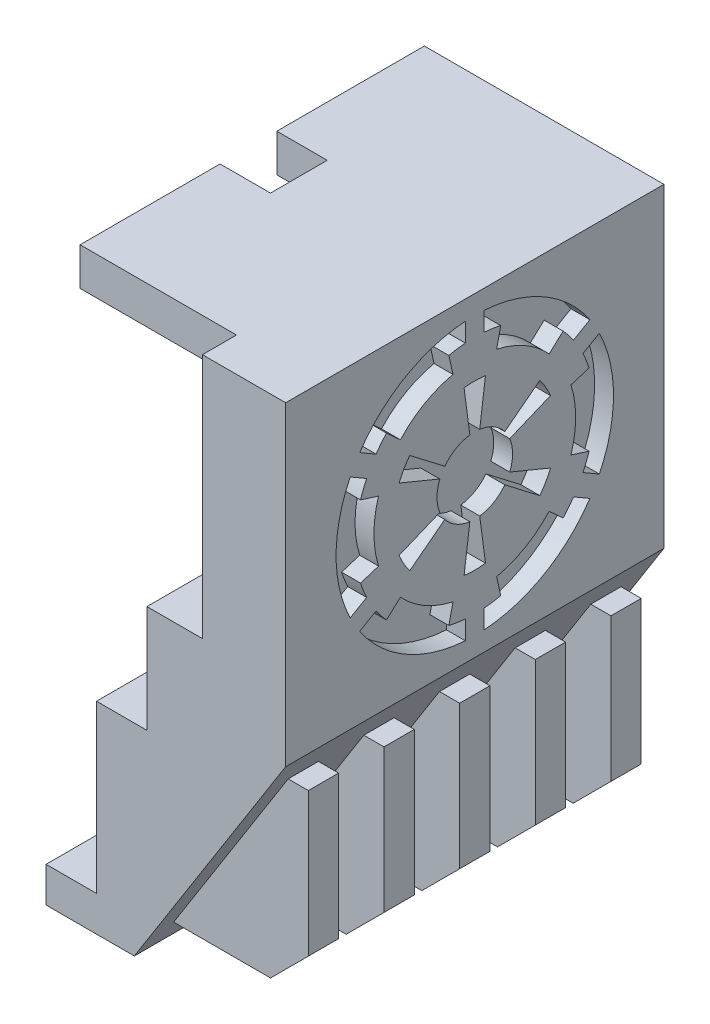
SolidWorks part; units mm, degrees
material "PE Low/Medium Density"
ref_plane "Front Plane" through (0, 0, 0) normal (0, 0, 1) x (1, 0, 0)
ref_plane "Top Plane" through (0, 0, 0) normal (0, 1, 0) x (1, 0, 0)
ref_plane "Right Plane" through (0, 0, 0) normal (1, 0, 0) x (0, 0, -1)
sketch "Sketch1" plane through (0, 0, 0) normal (1, 0, 0) x (0, 0, -1)
  line L2 (-15, -12.5) -> (15, -12.5)
  line L3 (-15, -12.5) -> (-15, 12.5)
  line L4 (-15, 12.5) -> (15, 12.5)
  line L5 (15, -12.5) -> (15, 12.5)
  line L6 (-15, -12.5) -> (15, 12.5) construction
  line L7 (-15, 12.5) -> (15, -12.5) construction
  point P1 (0, 0)
  dimension "D1" = 30
  dimension "D2" = 25
extrude "Boss-Extrude1" add sketch "Sketch1" along normal blind 3
sketch "Sketch2" plane through (0, 0, 0) normal (-1, 0, 0) x (0, 0, 1)
  line L0 (6, 9.5) -> (1.7, 9.5) construction
  line L1 (15, 12.5) -> (6, 12.5)
  line L2 (15, 12.5) -> (15, 9.5)
  line L3 (15, 9.5) -> (6, 9.5)
  line L4 (6, 12.5) -> (6, 9.5)
  line L5 (-15, 12.5) -> (15, 12.5) construction
  line L6 (1.7, 9.5) -> (-12.3, 9.5)
  line L7 (1.7, 9.5) -> (1.7, 12.5)
  line L8 (1.7, 12.5) -> (-12.3, 12.5)
  line L9 (-12.3, 9.5) -> (-12.3, 12.5)
  dimension "D1" = 9
  dimension "D2" = 3
  dimension "D3" = 4.3
  dimension "D4" = 14
extrude "Boss-Extrude2" add sketch "Sketch2" along normal blind 16
sketch "Sketch3" plane through (0, 0, 0) normal (-1, 0, 0) x (0, 0, 1)
  line L1 (1.7, 12.5) -> (6, 12.5)
  line L2 (1.7, 12.5) -> (1.7, 9.5)
  line L3 (1.7, 9.5) -> (6, 9.5)
  line L4 (6, 12.5) -> (6, 9.5)
extrude "Boss-Extrude3" add sketch "Sketch3" along normal blind 12
sketch "Sketch4" plane through (0, 0, 0) normal (-1, 0, 0) x (0, 0, 1)
  line L0 (15, 9.5) -> (15, -7) construction
  line L1 (15, 9.5) -> (15, -12.5) construction
  line L3 (15, -7) -> (-15, -7)
  line L4 (15, -7) -> (15, -12.5)
  line L5 (15, -12.5) -> (-15, -12.5)
  line L6 (-15, -7) -> (-15, -12.5)
  dimension "D1" = 16.5
extrude "Boss-Extrude4" add sketch "Sketch4" along normal blind 8
sketch "Sketch5" plane through (0, 0, 15) normal (0, 0, 1) x (1, 0, 0)
  line L0 (-8, -12.5) -> (-8, -31.5) construction
  line L1 (-12, -31.5) -> (-9, -31.5)
  line L2 (-9, -31.5) -> (3, -12.5)
  line L3 (3, -12.5) -> (-8, -12.5)
  line L4 (-8, -12.5) -> (-8, -15.5)
  line L5 (-8, -15.5) -> (-12, -15.5)
  line L6 (-12, -15.5) -> (-12, -31.5)
  line L7 (-9, -31.5) -> (-8, -31.5) construction
  dimension "D1" = 24.5
  dimension "D2" = 3
  dimension "D3" = 4
  dimension "D4" = 8.5
extrude "Boss-Extrude5" add sketch "Sketch5" against normal up to surface (30 mm away) up to face at (-1.6667, -2.3333, -15)
sketch "Sketch7" plane through (0, -31.5, 0) normal (0, -1, 0) x (1, 0, 0)
  line L0 (-9, -15) -> (-12, -15) construction
  line L1 (-12, 15) -> (-16, 15)
  line L2 (-12, 15) -> (-12, 6)
  line L3 (-12, 6) -> (-16, 6)
  line L4 (-16, 15) -> (-16, 6)
  line L5 (-12, 1.7) -> (-16, 1.7)
  line L6 (-12, 1.7) -> (-12, -15)
  line L7 (-12, -15) -> (-16, -15)
  line L8 (-16, 1.7) -> (-16, -15)
  line L9 (-16, -12.3) -> (-16, 1.7) construction
extrude "Boss-Extrude6" add sketch "Sketch7" against normal blind 3
sketch "Sketch9" plane through (0, 0, 15) normal (0, 0, 1) x (1, 0, 0)
  line L2 (0, -7) -> (-12, -7)
  line L3 (0, -7) -> (0, 9.5)
  line L4 (0, 9.5) -> (-12, 9.5)
  line L5 (-12, -7) -> (-12, 9.5)
sketch "Sketch10" plane through (7.7881, -4.9188, 0) normal (0.8455, -0.534, 0) x (0, 0, -1)
  line L0 (-7.2, -11.9666) -> (-7.2, -28.9666)
  line L1 (-13.2, -11.9666) -> (-10.8, -11.9666)
  line L2 (-13.2, -11.9666) -> (-13.2, -28.9666)
  line L3 (-13.2, -28.9666) -> (-10.8, -28.9666)
  line L4 (-10.8, -11.9666) -> (-10.8, -28.9666)
  line L5 (-7.2, -11.9666) -> (-4.8, -11.9666)
  line L6 (-4.8, -11.9666) -> (-4.8, -28.9666)
  line L7 (-7.2, -28.9666) -> (-4.8, -28.9666)
  line L8 (-1.2, -11.9666) -> (-1.2, -28.9666)
  line L9 (-1.2, -11.9666) -> (1.2, -11.9666)
  line L10 (1.2, -11.9666) -> (1.2, -28.9666)
  line L11 (-1.2, -28.9666) -> (1.2, -28.9666)
  line L12 (4.8, -11.9666) -> (4.8, -28.9666)
  line L13 (4.8, -11.9666) -> (7.2, -11.9666)
  line L14 (7.2, -11.9666) -> (7.2, -28.9666)
  line L15 (4.8, -28.9666) -> (7.2, -28.9666)
  line L16 (10.8, -11.9666) -> (10.8, -28.9666)
  line L17 (10.8, -11.9666) -> (13.2, -11.9666)
  line L18 (13.2, -11.9666) -> (13.2, -28.9666)
  line L19 (10.8, -28.9666) -> (13.2, -28.9666)
  line L20 (-15, -31.4388) -> (-15, -8.9666) construction
  line L25 (-15, -8.9666) -> (15, -8.9666) construction
  dimension "D1" = 5
  dimension "D2" = 2.4
  dimension "D3" = 1.8
  dimension "D4" = 17
  dimension "D5" = 3
sketch "Sketch11" plane through (3, 0, 0) normal (1, 0, 0) x (0, 0, -1)
  line L0 (-13.2, -15.0365) -> (-13.2, -29.4098) construction
  line L1 (-13.2, -29.4098) -> (-10.8, -29.4098) construction
  line L2 (-10.8, -15.0365) -> (-10.8, -29.4098) construction
  line L3 (-13.2, -15.0365) -> (-10.8, -15.0365) construction
  line L4 (-7.2, -15.0365) -> (-7.2, -29.4098) construction
  line L5 (-7.2, -29.4098) -> (-4.8, -29.4098) construction
  line L6 (-4.8, -15.0365) -> (-4.8, -29.4098) construction
  line L7 (-7.2, -15.0365) -> (-4.8, -15.0365) construction
  line L8 (-1.2, -15.0365) -> (-1.2, -29.4098) construction
  line L9 (-1.2, -29.4098) -> (1.2, -29.4098) construction
  line L10 (1.2, -15.0365) -> (1.2, -29.4098) construction
  line L11 (-1.2, -15.0365) -> (1.2, -15.0365) construction
  line L12 (4.8, -15.0365) -> (4.8, -29.4098) construction
  line L13 (4.8, -29.4098) -> (7.2, -29.4098) construction
  line L14 (7.2, -15.0365) -> (7.2, -29.4098) construction
  line L15 (4.8, -15.0365) -> (7.2, -15.0365) construction
  line L16 (10.8, -15.0365) -> (10.8, -29.4098) construction
  line L17 (10.8, -29.4098) -> (13.2, -29.4098) construction
  line L18 (13.2, -15.0365) -> (13.2, -29.4098) construction
  line L19 (10.8, -15.0365) -> (13.2, -15.0365) construction
  line L20 (-13.2, -15.0365) -> (-13.2, -29.4098)
  line L21 (-13.2, -29.4098) -> (-10.8, -29.4098)
  line L22 (-10.8, -15.0365) -> (-10.8, -29.4098)
  line L23 (-13.2, -15.0365) -> (-10.8, -15.0365)
  line L24 (-7.2, -15.0365) -> (-7.2, -29.4098)
  line L25 (-7.2, -29.4098) -> (-4.8, -29.4098)
  line L26 (-4.8, -15.0365) -> (-4.8, -29.4098)
  line L27 (-7.2, -15.0365) -> (-4.8, -15.0365)
  line L28 (-1.2, -15.0365) -> (-1.2, -29.4098)
  line L29 (-1.2, -29.4098) -> (1.2, -29.4098)
  line L30 (1.2, -15.0365) -> (1.2, -29.4098)
  line L31 (-1.2, -15.0365) -> (1.2, -15.0365)
  line L32 (4.8, -15.0365) -> (4.8, -29.4098)
  line L33 (4.8, -29.4098) -> (7.2, -29.4098)
  line L34 (7.2, -15.0365) -> (7.2, -29.4098)
  line L35 (4.8, -15.0365) -> (7.2, -15.0365)
  line L36 (10.8, -15.0365) -> (10.8, -29.4098)
  line L37 (10.8, -29.4098) -> (13.2, -29.4098)
  line L38 (13.2, -15.0365) -> (13.2, -29.4098)
  line L39 (10.8, -15.0365) -> (13.2, -15.0365)
  point P2 (-13.2, -22.2231)
extrude "Boss-Extrude8" add sketch "Sketch11" against normal up to surface (1.602 mm away)
chamfer "Chamfer1" distance 3 angle 45 5 edges at (3, -29.4098, -12) (3, -29.4098, -6) (3, -29.4098, 0) (3, -29.4098, 6) (3, -29.4098, 12)
sketch "Sketch12" plane through (3, 0, 0) normal (1, 0, 0) x (0, 0, -1)
  line L0 (0, 0) -> (0, 11) construction
  line L1 (-0.75, 10.9744) -> (-0.75, 9.4703)
  line L2 (0.75, 10.9744) -> (0.75, 9.4703)
  line L3 (-0.75, 9.4703) -> (0, 11) construction
  line L4 (0, 11) -> (0.75, 9.4703) construction
  line L5 (0, 0) -> (-3.5236, 15.8941) construction
  line L6 (0, 0) -> (3.5236, 15.8941) construction
  line L7 (3.5236, 15.8941) -> (0, 11) construction
  line L8 (0, 11) -> (-3.5236, 15.8941) construction
  line L9 (-3.5236, 15.8941) -> (3.5236, 15.8941) construction
  line L10 (-1.7315, 7.8104) -> (-2.0562, 9.2748)
  line L11 (1.7315, 7.8104) -> (2.0562, 9.2748)
  line L12 (0, 0) -> (-0.8484, 6.4444) construction
  line L13 (-0.8484, 6.4444) -> (0.8484, 6.4444) construction
  line L14 (0.8484, 6.4444) -> (0, 0) construction
  line L15 (-0.8484, 6.4444) -> (-0.3916, 2.9743)
  line L16 (0.8484, 6.4444) -> (0.3916, 2.9743)
  line L17 (9.1291, 6.1367) -> (7.8266, 5.3847)
  line L18 (9.8791, 4.8377) -> (8.5766, 4.0857)
  line L19 (5.8982, 5.4047) -> (7.0041, 6.4181)
  line L20 (7.6297, 2.4056) -> (9.0603, 2.8567)
  line L21 (5.1568, 3.9569) -> (2.3801, 1.8263)
  line L22 (6.0052, 2.4874) -> (2.7716, 1.1481)
  line L23 (9.8791, -4.8377) -> (8.5766, -4.0857)
  line L24 (9.1291, -6.1367) -> (7.8266, -5.3847)
  line L25 (7.6297, -2.4056) -> (9.0603, -2.8567)
  line L26 (5.8982, -5.4047) -> (7.0041, -6.4181)
  line L27 (6.0052, -2.4874) -> (2.7716, -1.1481)
  line L28 (5.1568, -3.9569) -> (2.3801, -1.8263)
  line L29 (0.75, -10.9744) -> (0.75, -9.4703)
  line L30 (-0.75, -10.9744) -> (-0.75, -9.4703)
  line L31 (1.7315, -7.8104) -> (2.0562, -9.2748)
  line L32 (-1.7315, -7.8104) -> (-2.0562, -9.2748)
  line L33 (0.8484, -6.4444) -> (0.3916, -2.9743)
  line L34 (-0.8484, -6.4444) -> (-0.3916, -2.9743)
  line L35 (-9.1291, -6.1367) -> (-7.8266, -5.3847)
  line L36 (-9.8791, -4.8377) -> (-8.5766, -4.0857)
  line L37 (-5.8982, -5.4047) -> (-7.0041, -6.4181)
  line L38 (-7.6297, -2.4056) -> (-9.0603, -2.8567)
  line L39 (-5.1568, -3.9569) -> (-2.3801, -1.8263)
  line L40 (-6.0052, -2.4874) -> (-2.7716, -1.1481)
  line L41 (-9.8791, 4.8377) -> (-8.5766, 4.0857)
  line L42 (-9.1291, 6.1367) -> (-7.8266, 5.3847)
  line L43 (-7.6297, 2.4056) -> (-9.0603, 2.8567)
  line L44 (-5.8982, 5.4047) -> (-7.0041, 6.4181)
  line L45 (-6.0052, 2.4874) -> (-2.7716, 1.1481)
  line L46 (-5.1568, 3.9569) -> (-2.3801, 1.8263)
  circle A0 centre (0, 0) radius 11
  circle A1 centre (0, 0) radius 9.5
  circle A2 centre (0, 0) radius 8
  circle A3 centre (0, 0) radius 6.5
  circle A4 centre (0, 0) radius 3
  point P0 (0, 6.4444)
  point P89 (0, 0)
  dimension "D1" = 22
  dimension "D2" = 1.5
  dimension "D6" = 1.5
  dimension "D7" = 25
  dimension "D8" = 15
  dimension "D9" = 6
  dimension "D3" = 1.5
  dimension "D4" = 1.5
  dimension "D5" = 3.5
extrude "Cut-Extrude1" cut sketch "Sketch12" against normal blind 1.5 contours A1 L1 A0 L42 | A1 L41 A0 L36 | A1 L35 A0 L30 | A1 L29 A0 L24 | A1 L23 A0 L18 | A1 L17 A0 L2 | A2 L10 A1 L44 | A2 L43 A1 L38 | A2 L37 A1 L32 | A2 L31 A1 L26 | A2 L25 A1 L20 | A2 L19 A1 L11 | A4 L46 A3 L45 | A4 L40 A3 L39 | A4 L34 A3 L33 | A4 L28 A3 L27 | A4 L22 A3 L21 | A4 L16 A3 L15 | A4
sketch "Sketch13" plane through (0, 0, 0) normal (-1, 0, 0) x (0, 0, 1)
  line L0 (15, -7) -> (-15, -7) construction
  line L1 (12.3, 12.5) -> (15, 12.5)
  line L2 (12.3, 12.5) -> (12.3, -7)
  line L3 (12.3, -7) -> (15, -7)
  line L4 (15, 12.5) -> (15, -7)
  line L5 (15, 9.5) -> (15, 12.5) construction
  dimension "D1" = 2.7
extrude "Boss-Extrude9" add sketch "Sketch13" along normal blind 3.6
sketch "Sketch15" plane through (0, 0, -15) normal (0, 0, -1) x (-1, 0, 0)
  line L4 (0, -7) -> (12, -7)
  line L5 (12, -7) -> (12, 9.5)
  line L6 (12, 9.5) -> (0, 9.5)
  line L7 (0, 9.5) -> (0, -7)
  line L8 (0, -7) -> (12, -7)
  line L9 (12, -7) -> (12, 9.5)
  line L10 (12, 9.5) -> (0, 9.5)
  line L11 (0, 9.5) -> (0, -7)
  dimension "D1" = 0
extrude "Boss-Extrude11" add sketch "Sketch15" against normal blind 2
sketch "Sketch16" plane through (0, 12.5, 0) normal (0, 1, 0) x (1, 0, 0)
  line L1 (-16, 15) -> (0.6792, 15)
  line L2 (-16, 15) -> (-16, -7.8401)
  line L3 (-16, -7.8401) -> (0.6792, -7.8401)
  line L4 (0.6792, 15) -> (0.6792, -7.8401)
extrude "Boss-Extrude12" add sketch "Sketch16" against normal up to surface (3 mm away) up to face at (-10.14, 9.5, 3.31)
sketch "Sketch17" plane through (0, 9.5, 0) normal (0, -1, 0) x (1, 0, 0)
  line L0 (-16, -15) -> (-16, 15) construction
  line L1 (-3.6, 15) -> (-16, 15)
  line L2 (-3.6, 15) -> (-3.6, 12.3)
  line L3 (-3.6, 12.3) -> (-16, 12.3)
  line L4 (-16, 15) -> (-16, 12.3)
extrude "Cut-Extrude2" cut sketch "Sketch17" against normal blind 13
sketch "Sketch18" plane through (0, 12.5, 0) normal (0, 1, 0) x (1, 0, 0)
  line L0 (-16, -12.3) -> (-16, 15) construction
  line L1 (-16, 3.3) -> (-12, 3.3)
  line L2 (-16, 3.3) -> (-16, -1.2)
  line L3 (-16, -1.2) -> (-12, -1.2)
  line L4 (-12, 3.3) -> (-12, -1.2)
  line L5 (3, 15) -> (-16, 15) construction
  line L7 (-12, 15) -> (-12, -15) construction
  dimension "D1" = 11.7
  dimension "D2" = 4.5
extrude "Cut-Extrude4" cut sketch "Sketch18" against normal through all
sketch "Sketch19" plane through (0, -31.5, 0) normal (0, -1, 0) x (1, 0, 0)
  line L1 (-16, 6) -> (-12, 6)
  line L2 (-16, 6) -> (-16, 1.7)
  line L3 (-16, 1.7) -> (-12, 1.7)
  line L4 (-12, 6) -> (-12, 1.7)
extrude "Boss-Extrude13" add sketch "Sketch19" against normal up to surface (3 mm away) up to face at (-14, -28.5, 10.5)
sketch "Sketch20" plane through (0, 0, -15) normal (0, 0, -1) x (-1, 0, 0)
  line L0 (12, -7) -> (12, 9.5) construction
  line L1 (8, -7) -> (12, -7)
  line L2 (8, -7) -> (8, -6)
  line L3 (8, -6) -> (12, -6)
  line L4 (12, -7) -> (12, -6)
  dimension "D1" = 1
extrude "Cut-Extrude5" cut sketch "Sketch20" against normal blind 13
sketch "Sketch21" plane through (0, 0, -15) normal (0, 0, -1) x (-1, 0, 0)
  line L0 (16, -28.5) -> (16, -31.5) construction
  line L1 (12, -28.5) -> (16, -28.5)
  line L2 (12, -28.5) -> (12, -28.7)
  line L3 (12, -28.7) -> (16, -28.7)
  line L4 (16, -28.5) -> (16, -28.7)
  dimension "D1" = 0.2
extrude "Cut-Extrude6" cut sketch "Sketch21" against normal through all
